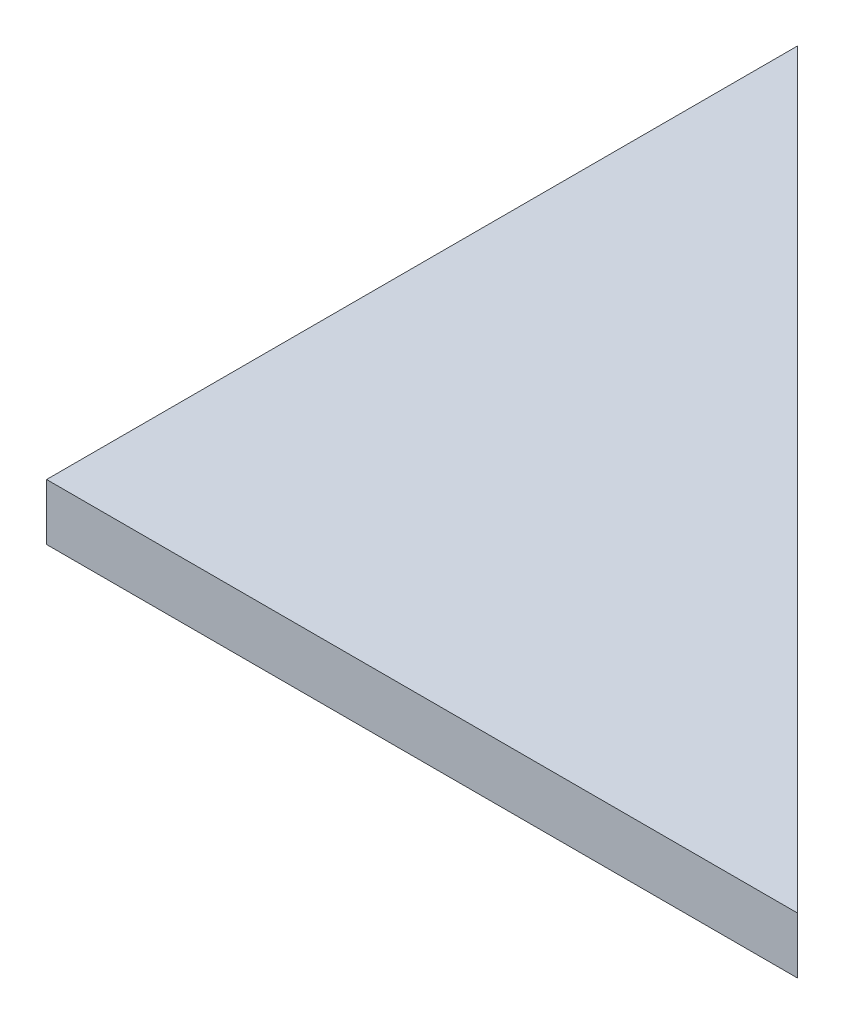
SolidWorks part; units mm, degrees
material "Thornel Mat VMA"
ref_plane "Front Plane" through (0, 0, 0) normal (0, 0, 1) x (1, 0, 0)
ref_plane "Top Plane" through (0, 0, 0) normal (0, 1, 0) x (1, 0, 0)
ref_plane "Right Plane" through (0, 0, 0) normal (1, 0, 0) x (0, 0, -1)
sketch "Sketch1" plane through (0, 0, 0) normal (0, 1, 0) x (1, 0, 0)
  line L0 (0, 0) -> (20, 0)
  line L1 (20, 0) -> (0, 20)
  line L2 (0, 20) -> (0, 0)
  dimension "D1" = 20
extrude "Boss-Extrude1" add sketch "Sketch1" along normal blind 1.5
